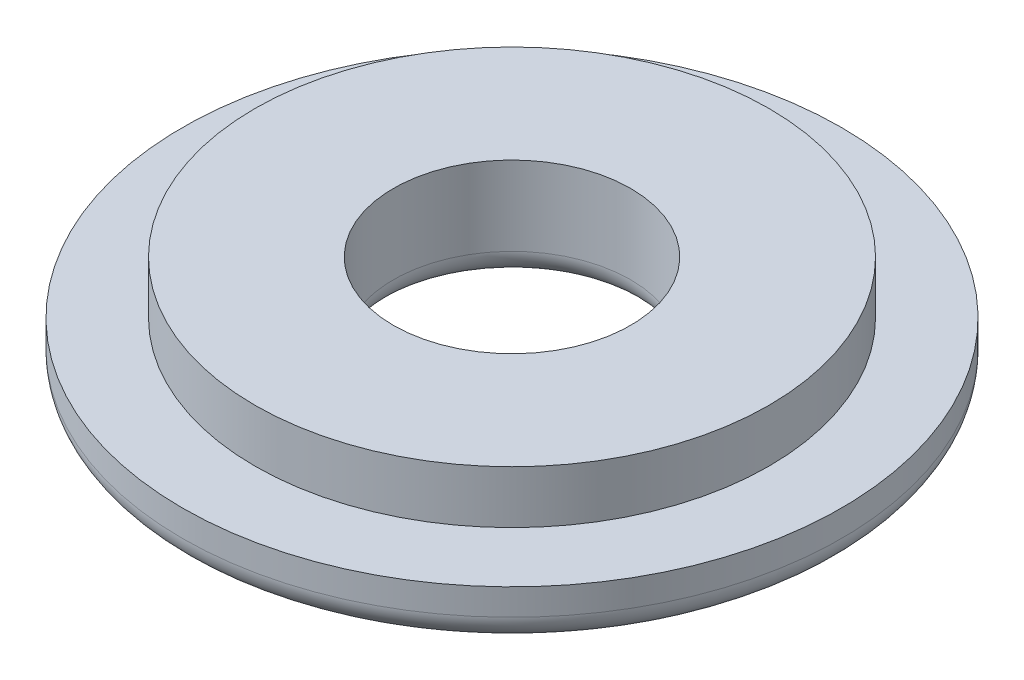
SolidWorks part; units mm, degrees
ref_plane "Front Plane" through (0, 0, 0) normal (0, 0, 1) x (1, 0, 0)
ref_plane "Top Plane" through (0, 0, 0) normal (0, 1, 0) x (1, 0, 0)
ref_plane "Right Plane" through (0, 0, 0) normal (1, 0, 0) x (0, 0, -1)
sketch "Sketch1" plane through (0, 0, 0) normal (0, 1, 0) x (1, 0, 0)
  circle A0 centre (0, 0) radius 12.5
  dimension "D1" = 25
extrude "Boss-Extrude1" add sketch "Sketch1" along normal blind 2 contours A0
sketch "Sketch2" plane through (0, 2, 0) normal (0, 1, 0) x (1, 0, 0)
  circle A0 centre (0, 0) radius 9.75
  dimension "D1" = 19.5
extrude "Boss-Extrude2" add sketch "Sketch2" along normal blind 2
sketch "Sketch3" plane through (0, 4, 0) normal (0, 1, 0) x (1, 0, 0)
  circle A0 centre (0, 0) radius 4.5
  dimension "D1" = 9
extrude "Cut-Extrude1" cut sketch "Sketch3" against normal through all
fillet "Fillet1" radius 1 2 edges at (0, 0, 4.5) (0, 0, 12.5)
